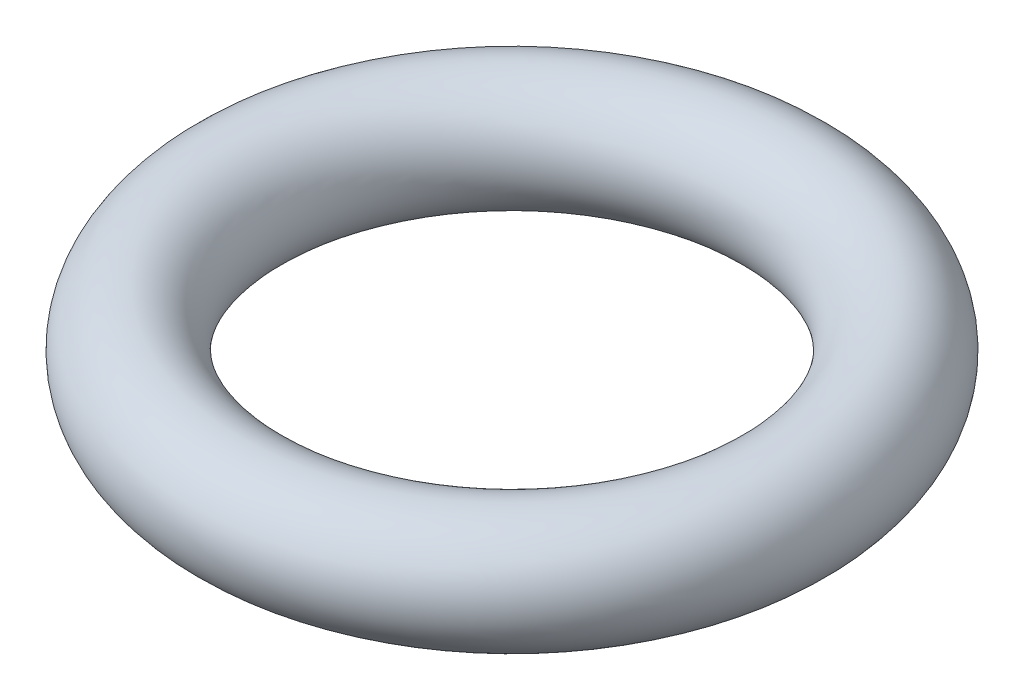
SolidWorks part; units mm, degrees
ref_plane "Plano frontal" through (0, 0, 0) normal (0, 0, 1) x (1, 0, 0)
ref_plane "Plano superior" through (0, 0, 0) normal (0, 1, 0) x (1, 0, 0)
ref_plane "Plano direito" through (0, 0, 0) normal (1, 0, 0) x (0, 0, -1)
sketch "Esboço1" plane through (0, 0, 0) normal (1, 0, 0) x (0, 0, -1)
  line L0 (0, 0) -> (0, 46.5706) construction
  circle A0 centre (-70, 0) radius 15
  dimension "D1" = 30
  dimension "D2" = 70
revolve "Revolução1" add sketch "Esboço1" angle 360 about L0
sketch "Esboço2" plane through (0, 0, 0) normal (1, 0, 0) x (0, 0, -1)
  line L0 (0, 0) -> (0, 37.7691) construction
  circle A0 centre (-70, 0) radius 10
  dimension "D1" = 20
  dimension "D2" = 70
revolve "Corte-Revolução1" cut sketch "Esboço2" angle 360 about L0
